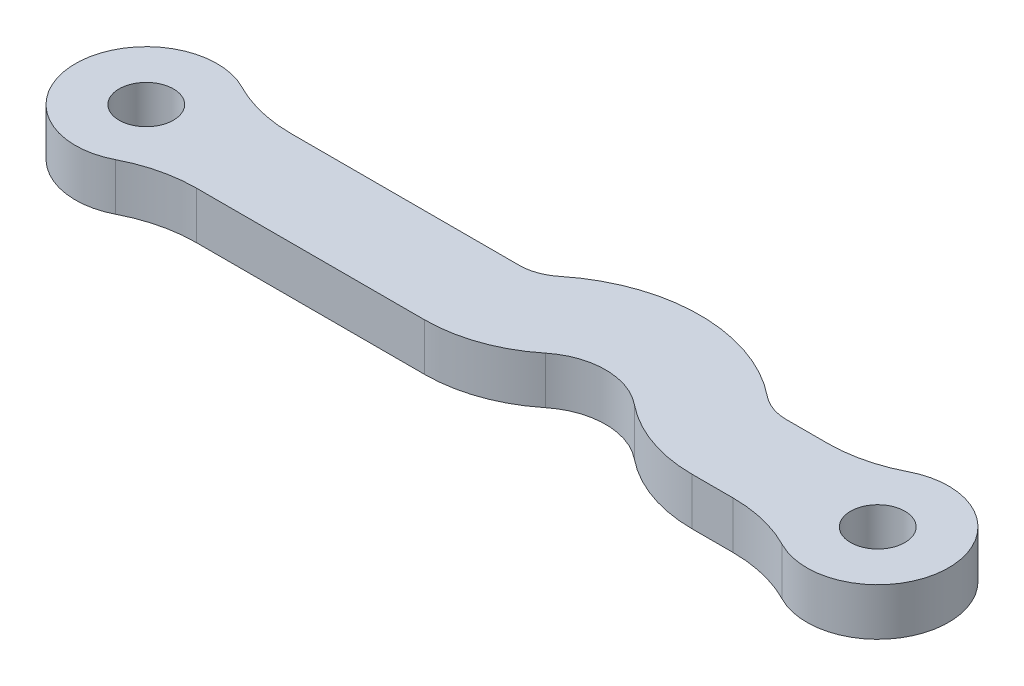
SolidWorks part; units mm, degrees
ref_plane "Спереди" through (0, 0, 0) normal (0, 0, 1) x (1, 0, 0)
ref_plane "Сверху" through (0, 0, 0) normal (0, 1, 0) x (1, 0, 0)
ref_plane "Справа" through (0, 0, 0) normal (1, 0, 0) x (0, 0, -1)
sketch "Эскиз1" plane through (0, 0, 0) normal (0, 1, 0) x (1, 0, 0)
  line L0 (0, 0) -> (30.95, 0) construction
  line L1 (2.2361, 2) -> (28.7139, 2)
  line L3 (28.7139, -2) -> (2.2361, -2)
  circle A0 centre (0, 0) radius 1.15
  arc A1 (2.2361, 2) -> (2.2361, -2) centre (0, 0) ccw
  circle A2 centre (30.95, 0) radius 1.15
  arc A3 (28.7139, -2) -> (28.7139, 2) centre (30.95, 0) ccw
  circle A4 centre (30.95, 0) radius 11.9 construction
  circle A5 centre (19.4344, -3) radius 3
  circle A6 centre (19.4344, -3) radius 7
  dimension "D4" = 2.3
  dimension "D5" = 2.3
  dimension "D6" = 6
  dimension "D7" = 6
  dimension "D8" = 23.8
  dimension "D9" = 6
  dimension "D10" = 14
  dimension "D1" = 30.95
  dimension "D2" = 2
  dimension "D3" = 2
extrude "Бобышка-Вытянуть1" add sketch "Эскиз1" along normal blind 2
fillet "Скругление1" radius 6 4 edges at (28.7139, 1, -2) (28.7139, 1, 2) (2.2361, 1, 2) (2.2361, 1, -2)
fillet "Скругление2" radius 6 2 edges at (22.2628, 1, 2) (16.6059, 1, 2)
fillet "Скругление3" radius 2 2 edges at (14.5354, 1, -2) (24.3333, 1, -2)
